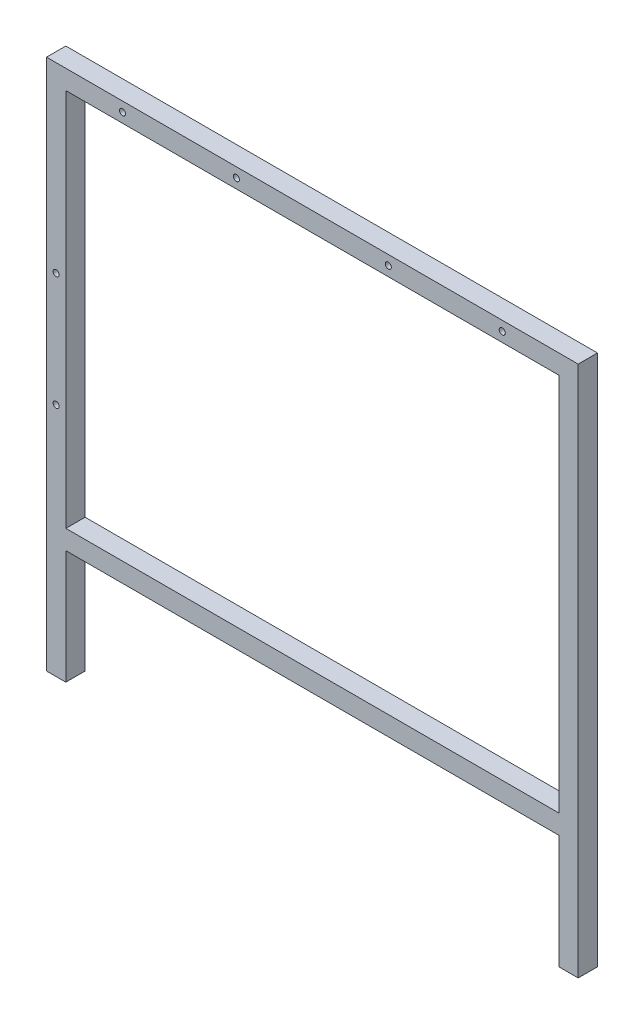
SolidWorks part; units mm, degrees
ref_plane "Front Plane" through (0, 0, 0) normal (0, 0, 1) x (1, 0, 0)
ref_plane "Top Plane" through (0, 0, 0) normal (0, 1, 0) x (1, 0, 0)
ref_plane "Right Plane" through (0, 0, 0) normal (1, 0, 0) x (0, 0, -1)
sketch "Sketch1" plane through (0, 0, 0) normal (0, 0, 1) x (1, 0, 0)
  line L0 (0, 0) -> (700, 0)
  line L1 (0, 0) -> (0, -700)
  line L3 (700, -700) -> (700, 0)
  line L4 (700, -700) -> (674.6, -700)
  line L5 (0, -700) -> (25.4, -700)
  line L6 (25.4, -700) -> (25.4, -25.4)
  line L7 (674.6, -700) -> (674.6, -25.4)
  line L8 (25.4, -25.4) -> (674.6, -25.4)
  line L9 (25.4, -550) -> (674.6, -550)
  line L10 (25.4, -524.6) -> (674.6, -524.6)
  line L11 (25.4, -25.4) -> (0, 0)
  line L12 (674.6, -25.4) -> (700, 0)
  dimension "D1" = 700
  dimension "D2" = 700
  dimension "D3" = 25.4
  dimension "D4" = 25.4
  dimension "D5" = 25.4
  dimension "D6" = 150
  dimension "D7" = 25.4
extrude "Boss-Extrude3" add sketch "Sketch1" against normal blind 25.4 contours L6 L11 L1 L5 | L8 L12 L0 L11 | L12 L7 L4 L3 | L10 L6 L9 L7
sketch "Sketch11" plane through (0, 0, 0) normal (0, 0, 1) x (1, 0, 0)
  line L0 (350, 23.3427) -> (250, 23.3427) construction
  line L1 (700, 23.3427) -> (600, 23.3427) construction
  line L2 (350, 23.3427) -> (450, 23.3427) construction
  line L5 (0, 0) -> (700, 0) construction
  line L6 (350, 37.9652) -> (0, 37.9652) construction
  line L7 (350, 37.9652) -> (700, 37.9652)
  line L8 (25.4, -25.4) -> (25.4, 0) construction
  line L9 (0, -12.7) -> (700, -12.7) construction
  line L10 (0, 0) -> (0, -700) construction
  line L11 (700, -700) -> (700, 0) construction
  line L12 (0, 23.3427) -> (100, 23.3427) construction
  circle A2 centre (100, -12.7) radius 4
  circle A3 centre (250, -12.7) radius 4
  circle A4 centre (600, -12.7) radius 4
  circle A5 centre (450, -12.7) radius 4
  dimension "D3" = 100
  dimension "D2" = 100
  dimension "D4" = 100
  dimension "D1" = 100
sketch "Sketch15" plane through (0, 0, 0) normal (0, 0, 1) x (1, 0, 0)
  line L0 (0, -700) -> (25.4, -700) construction
  line L1 (12.7, -700) -> (12.7, 0) construction
  line L2 (0, 0) -> (700, 0) construction
  line L3 (0, -700) -> (-55.862, -700) construction
  line L4 (-55.862, -700) -> (-55.862, -390) construction
  line L5 (-55.862, 0) -> (-55.862, -310) construction
  circle A0 centre (12.7, -240) radius 4
  circle A1 centre (12.7, -390) radius 4
  dimension "D3" = 150
  dimension "D1" = 310
  dimension "D2" = 310
extrude "Cut-Extrude5" cut sketch "Sketch15" against normal blind 25.4
extrude "Cut-Extrude7" cut sketch "Sketch11" against normal blind 25.4 contours A2 | A3 | A5 | A4
